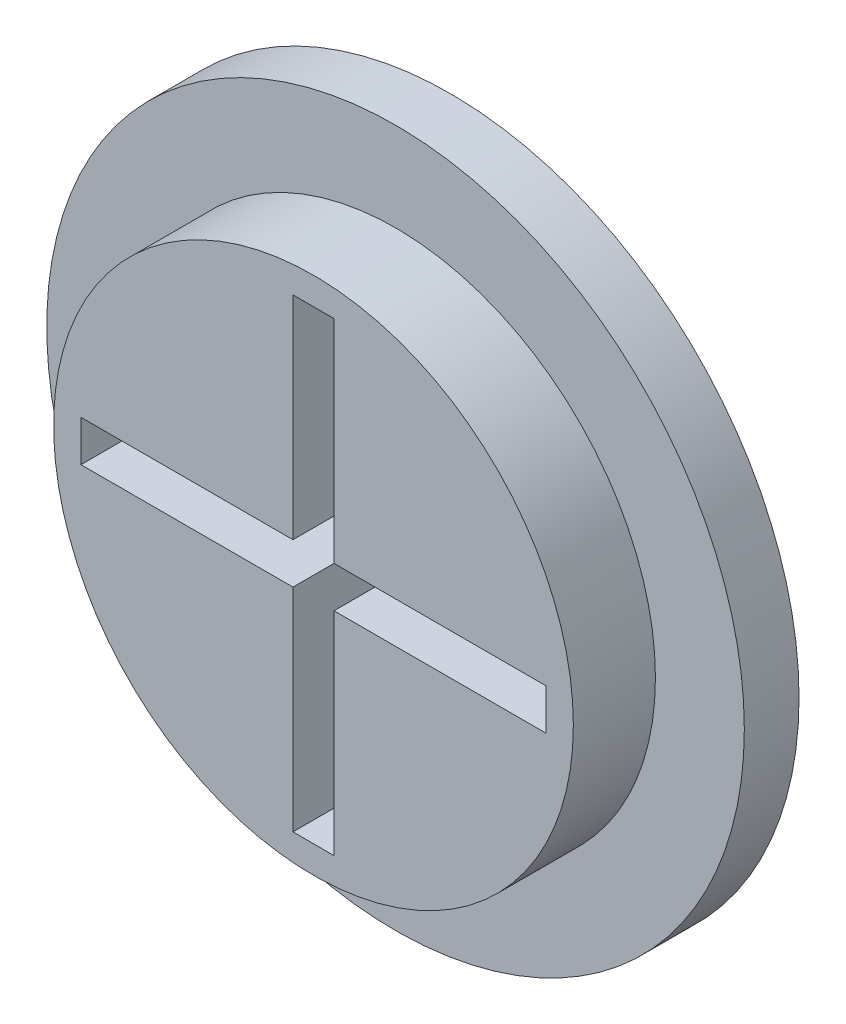
SolidWorks part; units mm, degrees
ref_plane "Přední rovina" through (0, 0, 0) normal (0, 0, 1) x (1, 0, 0)
ref_plane "Horní rovina" through (0, 0, 0) normal (0, 1, 0) x (1, 0, 0)
ref_plane "Pravá rovina" through (0, 0, 0) normal (1, 0, 0) x (0, 0, -1)
sketch "Outer sketch" plane through (0, 0, 0) normal (0, 0, 1) x (1, 0, 0)
  circle A0 centre (0, 0) radius 12.75
  dimension "D1" = 25.5
extrude "Outer" add sketch "Outer sketch" along normal blind 2
sketch "Inner sketch" plane through (0, 0, 2) normal (0, 0, 1) x (1, 0, 0)
  circle A0 centre (0, 0) radius 9.5
  dimension "D1" = 19
extrude "Inner" add sketch "Inner sketch" along normal blind 3
sketch "Cut out sketch" plane through (0, 0, 5) normal (0, 0, 1) x (1, 0, 0)
  line L1 (-8.5, 0.75) -> (8.5, 0.75)
  line L2 (-8.5, 0.75) -> (-8.5, -0.75)
  line L3 (-8.5, -0.75) -> (8.5, -0.75)
  line L4 (8.5, 0.75) -> (8.5, -0.75)
  line L5 (-8.5, 0.75) -> (8.5, -0.75) construction
  line L6 (-8.5, -0.75) -> (8.5, 0.75) construction
  line L7 (-0.75, 8.5) -> (0.75, 8.5)
  line L8 (-0.75, 8.5) -> (-0.75, -8.5)
  line L9 (-0.75, -8.5) -> (0.75, -8.5)
  line L10 (0.75, 8.5) -> (0.75, -8.5)
  line L11 (-0.75, 8.5) -> (0.75, -8.5) construction
  line L12 (-0.75, -8.5) -> (0.75, 8.5) construction
  point P0 (0, 0)
  point P6 (0, 0)
  dimension "D1" = 17
  dimension "D2" = 1.5
  dimension "D3" = 17
  dimension "D4" = 1.5
extrude "Odebrat vysunutím1" cut sketch "Cut out sketch" against normal through all contours L8 L1 L2 L3 | L10 L7 L8 L1 | L10 L1 L8 L3 | L10 L3 L8 L9 | L1 L10 L3 L4
